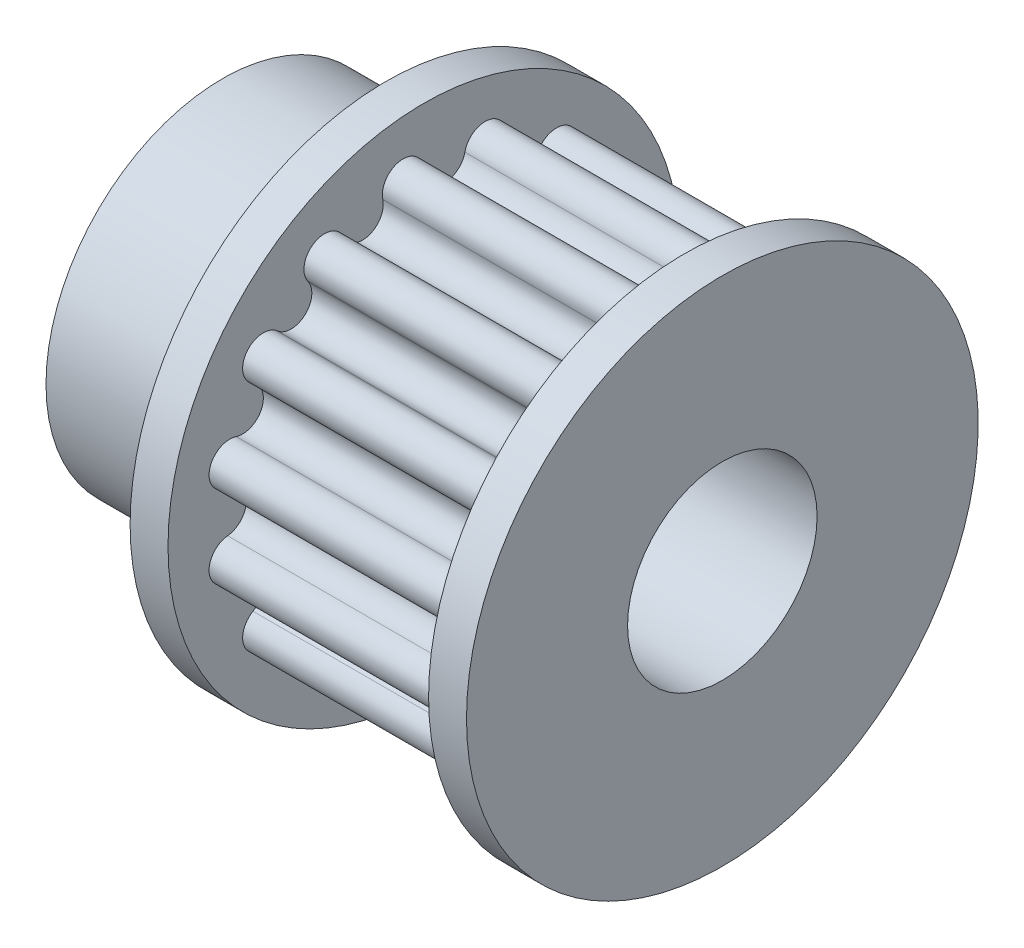
SolidWorks part; units mm, degrees
ref_plane "Front Plane" through (0, 0, 0) normal (0, 0, 1) x (1, 0, 0)
ref_plane "Top Plane" through (0, 0, 0) normal (0, 1, 0) x (1, 0, 0)
ref_plane "Right Plane" through (0, 0, 0) normal (1, 0, 0) x (0, 0, -1)
sketch "Sketch1" plane through (0, 0, 0) normal (0, 0, 1) x (1, 0, 0)
  line L0 (0, 4) -> (0, 7.45)
  line L1 (0, 7.45) -> (6.9, 7.45)
  line L2 (6.9, 7.45) -> (6.9, 10.8)
  line L3 (6.9, 10.8) -> (8.5, 10.8)
  line L4 (8.5, 10.8) -> (8.5, 9.25)
  line L5 (8.5, 9.25) -> (19.5, 9.25)
  line L6 (19.5, 9.25) -> (19.5, 10.8)
  line L7 (19.5, 10.8) -> (21.1, 10.8)
  line L8 (21.1, 10.8) -> (21.1, 4)
  line L10 (0, 4) -> (21.1, 4)
  line L11 (0, 0) -> (31.2779, 0)
  point P11 (0, 0)
  point P15 (0, 0)
  dimension "D1" = 21.1
  dimension "D2" = 3.45
  dimension "D3" = 6.9
  dimension "D4" = 11
  dimension "D5" = 6.8
  dimension "D6" = 3.35
  dimension "D7" = 1.55
  dimension "D8" = 1.6
revolve "Revolve2" add sketch "Sketch1" angle 360 about L11
sketch "Sketch4" plane through (8.5, 0, 0) normal (1, 0, 0) x (0, 0, -1)
  circle A0 centre (0, 0) radius 9.25
  arc A1 (0, 8.3287) -> (-1.7316, 8.1467) centre (-0.8754, 8.3287) ccw
  arc A2 (0, 8.3287) -> (1.7316, 8.1467) centre (0.8754, 8.3287) ccw
  arc A3 (3.3876, 7.6087) -> (1.7316, 8.1467) centre (2.5879, 7.9647) ccw
  arc A4 (6.1895, 5.573) -> (4.8955, 6.7381) centre (5.6037, 6.2236) ccw
  arc A5 (7.9211, 2.5737) -> (7.2129, 4.1644) centre (7.6506, 3.4063) ccw
  arc A6 (8.2831, -0.8706) -> (8.2831, 0.8706) centre (8.3746, 0) ccw
  arc A7 (7.2129, -4.1644) -> (7.9211, -2.5737) centre (7.6506, -3.4063) ccw
  arc A8 (4.8955, -6.7381) -> (6.1895, -5.573) centre (5.6037, -6.2236) ccw
  arc A9 (1.7316, -8.1467) -> (3.3876, -7.6087) centre (2.5879, -7.9647) ccw
  arc A10 (-1.7316, -8.1467) -> (0, -8.3287) centre (-0.8754, -8.3287) ccw
  arc A11 (-4.8955, -6.7381) -> (-3.3876, -7.6087) centre (-4.1873, -7.2526) ccw
  arc A12 (-7.2129, -4.1644) -> (-6.1895, -5.573) centre (-6.7752, -4.9225) ccw
  arc A13 (-8.2831, -0.8706) -> (-7.9211, -2.5737) centre (-8.1916, -1.7412) ccw
  arc A14 (-7.9211, 2.5737) -> (-8.2831, 0.8706) centre (-8.1916, 1.7412) ccw
  arc A15 (-6.1895, 5.573) -> (-7.2129, 4.1644) centre (-6.7752, 4.9225) ccw
  arc A16 (-3.3876, 7.6087) -> (-4.8955, 6.7381) centre (-4.1873, 7.2526) ccw
  arc A17 (3.3876, 7.6087) -> (4.8955, 6.7381) centre (4.1873, 7.2526) ccw
  arc A18 (6.1895, 5.573) -> (7.2129, 4.1644) centre (6.7752, 4.9225) ccw
  arc A19 (7.9211, 2.5737) -> (8.2831, 0.8706) centre (8.1916, 1.7412) ccw
  arc A20 (8.2831, -0.8706) -> (7.9211, -2.5737) centre (8.1916, -1.7412) ccw
  arc A21 (7.2129, -4.1644) -> (6.1895, -5.573) centre (6.7752, -4.9225) ccw
  arc A22 (4.8955, -6.7381) -> (3.3876, -7.6087) centre (4.1873, -7.2526) ccw
  arc A23 (1.7316, -8.1467) -> (0, -8.3287) centre (0.8754, -8.3287) ccw
  arc A24 (-1.7316, -8.1467) -> (-3.3876, -7.6087) centre (-2.5879, -7.9647) ccw
  arc A25 (-4.8955, -6.7381) -> (-6.1895, -5.573) centre (-5.6037, -6.2236) ccw
  arc A26 (-7.2129, -4.1644) -> (-7.9211, -2.5737) centre (-7.6506, -3.4063) ccw
  arc A27 (-8.2831, -0.8706) -> (-8.2831, 0.8706) centre (-8.3746, 0) ccw
  arc A28 (-7.9211, 2.5737) -> (-7.2129, 4.1644) centre (-7.6506, 3.4063) ccw
  arc A29 (-6.1895, 5.573) -> (-4.8955, 6.7381) centre (-5.6037, 6.2236) ccw
  arc A30 (-3.3876, 7.6087) -> (-1.7316, 8.1467) centre (-2.5879, 7.9647) ccw
  point P3 (0, 0)
  point P35 (0, 0)
  point P65 (0, 0)
  point P124 (0, 0)
  circle M31 centre (0, 0) radius 9.25
  dimension "D1" = 18.5
  dimension "D2" = 15
  dimension "D3" = 15
extrude "Cut-Extrude1" cut sketch "Sketch4" along normal blind 11 contours A4 A18 A5 M31 | A5 A19 A6 A0 | A6 A20 A7 M31 | A7 A21 A8 A0 | A8 A22 A9 M31 | A9 A23 A10 A0 | A10 A24 A11 M31 | A11 A25 A12 A0 | A12 A26 A13 M31 | A13 A27 A14 A0 | A14 A28 A15 M31 | A15 A29 A16 A0 | A16 A30 A1 M31 | A3 A1 A2 M31 | A3 A17 A4 A0
